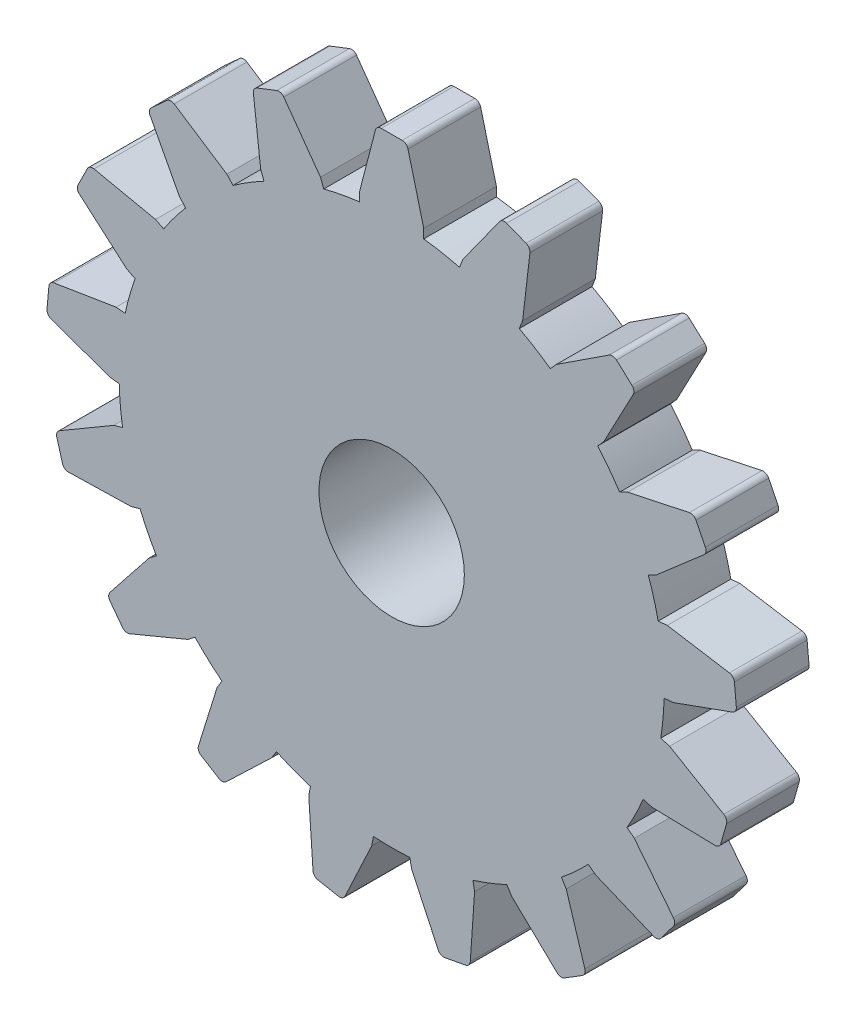
SolidWorks part; units mm, degrees
ref_plane "Front Plane" through (0, 0, 0) normal (0, 0, 1) x (1, 0, 0)
ref_plane "Top Plane" through (0, 0, 0) normal (0, 1, 0) x (1, 0, 0)
ref_plane "Right Plane" through (0, 0, 0) normal (1, 0, 0) x (0, 0, -1)
sketch "Sketch1" plane through (0, 0, 0) normal (0, 0, 1) x (1, 0, 0)
  circle A0 centre (0, 0) radius 11.25
  circle A1 centre (0, 0) radius 3
  dimension "D3" = 6
  dimension "D4" = 22.5
extrude "Boss-Extrude1" add sketch "Sketch1" along normal blind 3 contours A0 A1
sketch "Sketch2" plane through (0, 0, 0) normal (0, 0, 1) x (1, 0, 0)
  line L0 (-1.3233, 10.75) -> (-1.3233, 11.55)
  line L1 (-1.3233, 11.55) -> (-0.625, 14.25)
  line L2 (-0.625, 14.25) -> (0.625, 14.25)
  line L3 (0.625, 14.25) -> (1.3233, 11.55)
  line L4 (1.3233, 11.55) -> (1.3233, 10.75)
  line L5 (1.3233, 10.75) -> (-1.3233, 10.75)
  point P7 (0, 10.75)
  dimension "D1" = 0.8
  dimension "D2" = 3.5
  dimension "D3" = 14.5
  dimension "D4" = 14.5
  dimension "D5" = 1.25
  dimension "D6" = 10.75
extrude "Boss-Extrude2" add sketch "Sketch2" along normal up to surface (3 mm away) up to face at (3, 0, 3)
fillet "Fillet1" radius 0.25 2 edges at (0.625, 14.25, 1.5) (-0.625, 14.25, 1.5)
pattern_circular "CirPattern1" count 17 over 360 about axis through (0, 0, 0) along (0, 0, 1) of "Boss-Extrude2", "Fillet1"
sketch "Sketch3" plane through (0, 0, 0) normal (0, 0, 1) x (1, 0, 0)
  circle A0 centre (0, 0) radius 3 construction
  circle A1 centre (0, 0) radius 3
  circle A2 centre (0, 0) radius 5
  dimension "D1" = 2
extrude "Boss-Extrude3" add sketch "Sketch3" against normal blind 3.5
